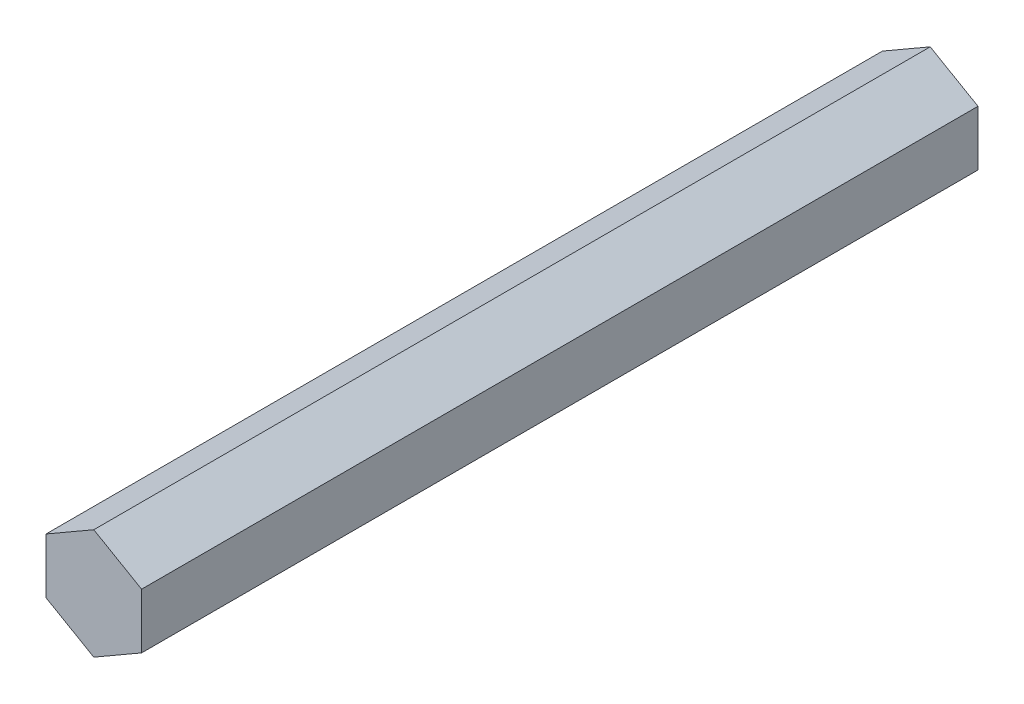
SolidWorks part; units mm, degrees
ref_plane "Front Plane" through (0, 0, 0) normal (0, 0, 1) x (1, 0, 0)
ref_plane "Top Plane" through (0, 0, 0) normal (0, 1, 0) x (1, 0, 0)
ref_plane "Right Plane" through (0, 0, 0) normal (1, 0, 0) x (0, 0, -1)
sketch "Sketch1" plane through (0, 0, 0) normal (0, 0, 1) x (1, 0, 0)
  line L0 (-6.35, 0) -> (6.35, 0) construction
  line L9 (0, 7.3323) -> (-6.35, 3.6662) construction
  line L10 (-6.35, 3.6662) -> (-6.35, -3.6662) construction
  line L11 (-6.35, -3.6662) -> (0, -7.3323) construction
  line L12 (0, -7.3323) -> (6.35, -3.6662) construction
  line L13 (6.35, -3.6662) -> (6.35, 3.6662) construction
  line L14 (6.35, 3.6662) -> (0, 7.3323) construction
  circle A3 centre (0, 0) radius 6.35 construction
  point P4 (0, 0)
  dimension "Width" = 12.7
sketch "Sketch2" plane through (0, 0, 0) normal (1, 0, 0) x (0, 0, -1)
  line L0 (63.5, 7.3323) -> (-63.5, 7.3323) construction
  point P3 (-48.895, 7.3323)
  point P4 (0, 7.3323)
  point P5 (48.895, 7.3323)
  dimension "Length" = 127
  dimension "D1" = 14.605
  dimension "D2" = 14.605
sketch "Sketch3" plane through (0, 0, 0) normal (0, 0, 1) x (1, 0, 0)
  line L1 (0, 7.3323) -> (6.35, 3.6662)
  line L2 (6.35, 3.6662) -> (6.35, -3.6662)
  line L3 (6.35, -3.6662) -> (0, -7.3323)
  line L4 (0, -7.3323) -> (-6.35, -3.6662)
  line L5 (-6.35, -3.6662) -> (-6.35, 3.6662)
  line L6 (-6.35, 3.6662) -> (0, 7.3323)
extrude "Boss-Extrude1" add sketch "Sketch3" along normal mid plane 111.125
equation "\"D1@Boss-Extrude1\"=\"A\""
equation "\"D1@Sketch2\" = \"Width@Sketch1\" * 1.15"
equation "\"D2@Sketch2\"=\"D1@Sketch2\""
equation "\"A\"=4.375"
